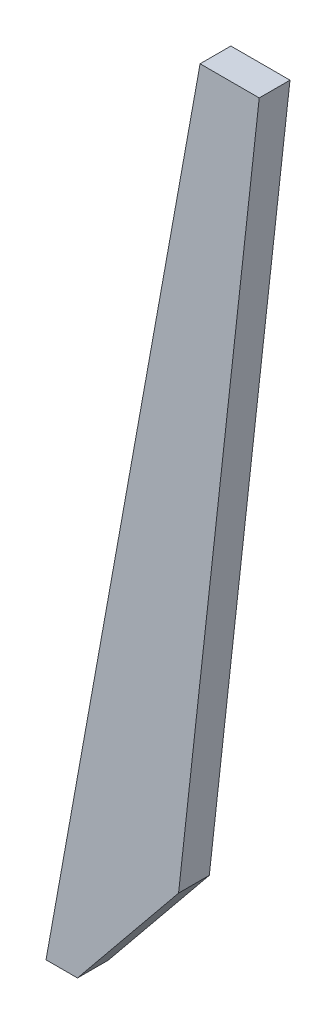
SolidWorks part; units mm, degrees
ref_plane "Front Plane" through (0, 0, 0) normal (0, 0, 1) x (1, 0, 0)
ref_plane "Top Plane" through (0, 0, 0) normal (0, 1, 0) x (1, 0, 0)
ref_plane "Right Plane" through (0, 0, 0) normal (1, 0, 0) x (0, 0, -1)
sketch "Sketch3" plane through (0, 0, 0) normal (0, 0, 1) x (1, 0, 0)
  line L0 (400.5772, 416) -> (361.2334, 60.4896)
  line L1 (311.9448, 0) -> (296.5972, 0)
  line L3 (296.5972, 0) -> (371.7349, 416)
  line L5 (371.7349, 416) -> (400.5772, 416)
  line L6 (329.2398, 180.7256) -> (374.5398, 180.7256) construction
  line L7 (311.9448, 0) -> (361.2334, 60.4896)
  dimension "D1" = 45.3
extrude "Boss-Extrude1" add sketch "Sketch3" along normal blind 15
scale "Scale1" scale about centroid uniform scaling yes scale factor 0.6
